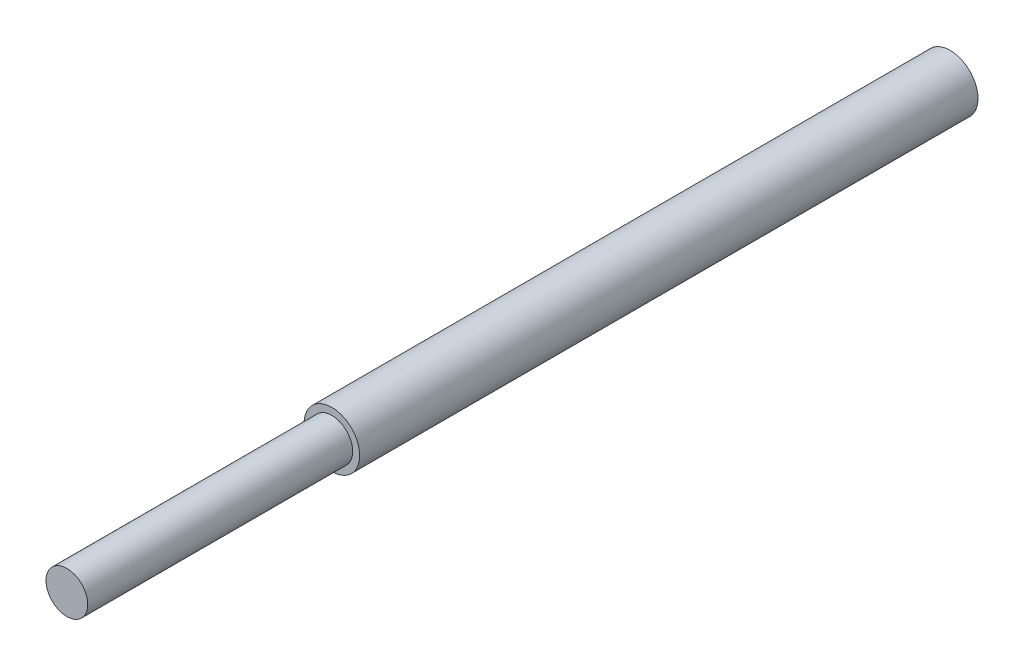
SolidWorks part; units mm, degrees
ref_plane "Front Plane" through (0, 0, 0) normal (0, 0, 1) x (1, 0, 0)
ref_plane "Top Plane" through (0, 0, 0) normal (0, 1, 0) x (1, 0, 0)
ref_plane "Right Plane" through (0, 0, 0) normal (1, 0, 0) x (0, 0, -1)
sketch "Sketch1" plane through (0, 0, 0) normal (0, 0, 1) x (1, 0, 0)
  circle A0 centre (0, 0) radius 4
  dimension "D1" = 8
extrude "Boss-Extrude1" add sketch "Sketch1" along normal blind 88.9
sketch "Sketch2" plane through (0, 0, 88.9) normal (0, 0, 1) x (1, 0, 0)
  circle A0 centre (0, 0) radius 3
  dimension "D1" = 6
extrude "Boss-Extrude2" add sketch "Sketch2" along normal blind 38.1
